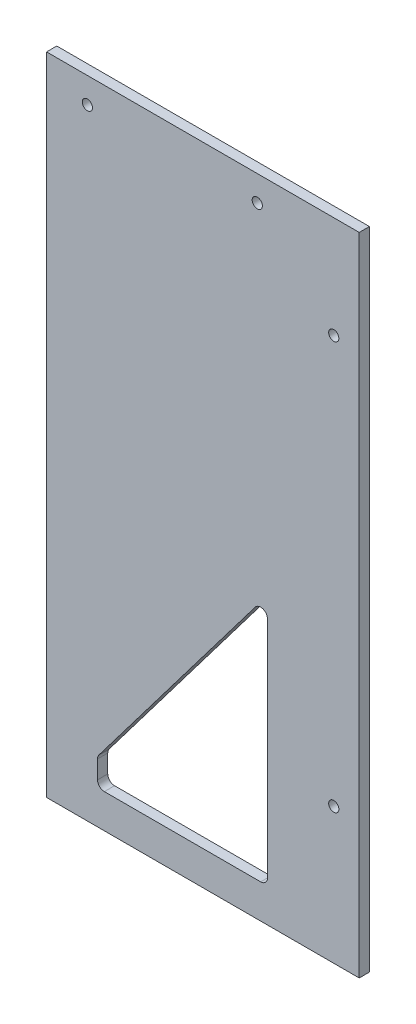
SolidWorks part; units mm, degrees
material "环氧树脂,未充填"
ref_plane "前视基准面" through (0, 0, 0) normal (0, 0, 1) x (1, 0, 0)
ref_plane "上视基准面" through (0, 0, 0) normal (0, 1, 0) x (1, 0, 0)
ref_plane "右视基准面" through (0, 0, 0) normal (1, 0, 0) x (0, 0, -1)
sketch "草图1" plane through (0, 0, 0) normal (0, 0, 1) x (1, 0, 0)
  line L1 (-46, 95) -> (46, 95)
  line L2 (-46, 95) -> (-46, -95)
  line L3 (-46, -95) -> (46, -95)
  line L4 (46, 95) -> (46, -95)
  line L5 (-46, 95) -> (46, -95) construction
  line L6 (-46, -95) -> (46, 95) construction
  point P0 (0, 0)
  dimension "D1" = 92
  dimension "D2" = 190
extrude "凸台-拉伸1" add sketch "草图1" along normal blind 3
sketch "草图2" plane through (0, 0, 3) normal (0, 0, 1) x (1, 0, 0)
  line L0 (-46, 87.5) -> (46, 87.5) construction
  line L1 (-46, 95) -> (-46, -95) construction
  line L2 (46, -95) -> (46, 95) construction
  line L3 (46, 95) -> (-46, 95) construction
  line L4 (38.5, 95) -> (38.5, -95) construction
  line L5 (-46, -95) -> (46, -95) construction
  circle A0 centre (-34, 87.5) radius 1.5
  circle A1 centre (16, 87.5) radius 1.5
  circle A2 centre (38.5, 65) radius 1.5
  circle A3 centre (38.5, -55) radius 1.5
  dimension "D3" = 30
  dimension "D5" = 3
  dimension "D1" = 7.5
  dimension "D2" = 7.5
  dimension "D4" = 50
  dimension "D6" = 30
  dimension "D7" = 120
extrude "切除-拉伸1" cut sketch "草图2" against normal through all
sketch "草图3" plane through (0, 0, 3) normal (0, 0, 1) x (1, 0, 0)
  line L0 (-46, -95) -> (46, -95) construction
  line L1 (-31, -15) -> (19, -15)
  line L2 (-31, -15) -> (-31, -85)
  line L3 (-31, -85) -> (19, -85)
  line L4 (19, -15) -> (19, -85)
  line L5 (-46, 95) -> (-46, -95) construction
  line L6 (-31, -77) -> (16, -15)
  dimension "D1" = 70
  dimension "D2" = 50
  dimension "D3" = 10
  dimension "D4" = 15
  dimension "D5" = 3
  dimension "D6" = 8
extrude "切除-拉伸2" cut sketch "草图3" against normal through all
fillet "圆角2" radius 2 5 edges at (19, -85, 1.5) (-31, -85, 1.5) (-31, -77, 1.5) (16, -15, 1.5) (19, -15, 1.5)
